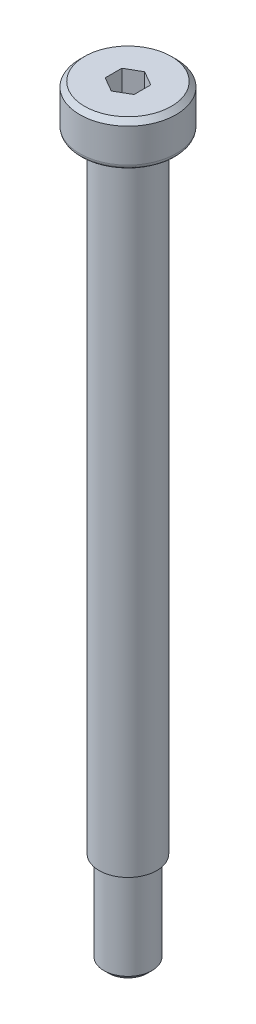
SolidWorks part; units mm, degrees
material "Plain Carbon Steel"
ref_plane "Front Plane" through (0, 0, 0) normal (0, 0, 1) x (1, 0, 0)
ref_plane "Top Plane" through (0, 0, 0) normal (0, 1, 0) x (1, 0, 0)
ref_plane "Right Plane" through (0, 0, 0) normal (1, 0, 0) x (0, 0, -1)
sketch "Sketch1" plane through (0, 0, 0) normal (0, 0, 1) x (1, 0, 0)
  line L0 (0, 0) -> (5, 0)
  line L1 (5, 0) -> (5, -4.5)
  line L2 (5, -4.5) -> (2.75, -4.5)
  line L3 (2.75, -4.5) -> (2.75, -4.75)
  line L4 (2.75, -4.75) -> (3, -4.75)
  line L5 (3, -4.75) -> (3, -69.5)
  line L6 (3, -69.5) -> (2.5, -69.5)
  line L7 (2.5, -69.5) -> (2.5, -79.25)
  line L8 (2.5, -79.25) -> (0, -79.25)
  line L9 (0, -79.25) -> (0, 0)
  line L10 (0, 5) -> (0, -84.25) construction
  dimension "D1" = 5
  dimension "D2" = 5
  dimension "D3" = 5
  dimension "D4" = 6
  dimension "D5" = 0.25
  dimension "D6" = 10
  dimension "Length" = 65
  dimension "D8" = 4.5
  dimension "D9" = 0.25
  dimension "D10" = 9.75
revolve "Revolve1" add sketch "Sketch1" angle 360 about L10
sketch "Sketch2" plane through (0, 0, 0) normal (0, 1, 0) x (1, 0, 0)
  line L1 (0, -1.7321) -> (1.5, -0.866)
  line L2 (1.5, -0.866) -> (1.5, 0.866)
  line L3 (1.5, 0.866) -> (0, 1.7321)
  line L4 (0, 1.7321) -> (-1.5, 0.866)
  line L5 (-1.5, 0.866) -> (-1.5, -0.866)
  line L6 (-1.5, -0.866) -> (0, -1.7321)
  circle A0 centre (0, 0) radius 1.5 construction
  dimension "D1" = 3
extrude "Cut-Extrude1" cut sketch "Sketch2" against normal blind 2.5
chamfer "Chamfer1" distance 0.5 angle 45 1 edges at (-5, 0, 0)
fillet "Fillet1" radius 0.5 1 edges at (-5, -4.5, 0)
chamfer "Chamfer2" distance 0.5 angle 45 1 edges at (-2.5, -79.25, 0)
